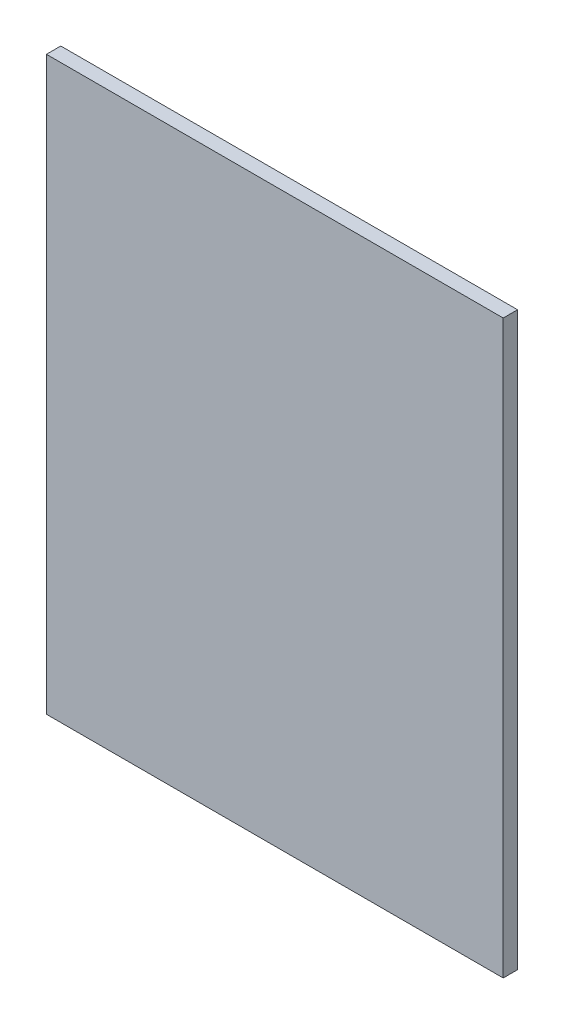
SolidWorks part; units mm, degrees
ref_plane "Front" through (0, 0, 0) normal (0, 0, 1) x (1, 0, 0)
ref_plane "Top" through (0, 0, 0) normal (0, 1, 0) x (1, 0, 0)
ref_plane "Right" through (0, 0, 0) normal (1, 0, 0) x (0, 0, -1)
sketch "草图1" plane through (0, 0, 0) normal (0, 0, 1) x (1, 0, 0)
  line L1 (-1990, 2490) -> (1990, 2490)
  line L2 (-1990, 2490) -> (-1990, -2490)
  line L3 (-1990, -2490) -> (1990, -2490)
  line L4 (1990, 2490) -> (1990, -2490)
  line L5 (-1990, 2490) -> (1990, -2490) construction
  line L6 (-1990, -2490) -> (1990, 2490) construction
  point P0 (0, 0)
extrude "凸台-拉伸1" add sketch "草图1" along normal blind 125
sketch "草图2" plane through (-1990, 0, 0) normal (-1, 0, 0) x (0, 0, 1)
  line L0 (62.5, 2490) -> (62.5, -2490)
  line L1 (125, 2490) -> (0, 2490) construction
  line L2 (125, -2490) -> (0, -2490) construction
sketch "草图3" plane through (0, 0, 0) normal (0, 0, -1) x (-1, 0, 0)
  circle A0 centre (-278.9409, -104.7035) radius 68.3929
  point P0 (-278.9409, -104.7035)
sketch "草图5" plane through (0, 0, 125) normal (0, 0, 1) x (1, 0, 0)
  circle A1 centre (278.9409, -104.7035) radius 68.3929
  point P0 (278.9409, -104.7035)
  point P1 (278.9409, -104.7035)
